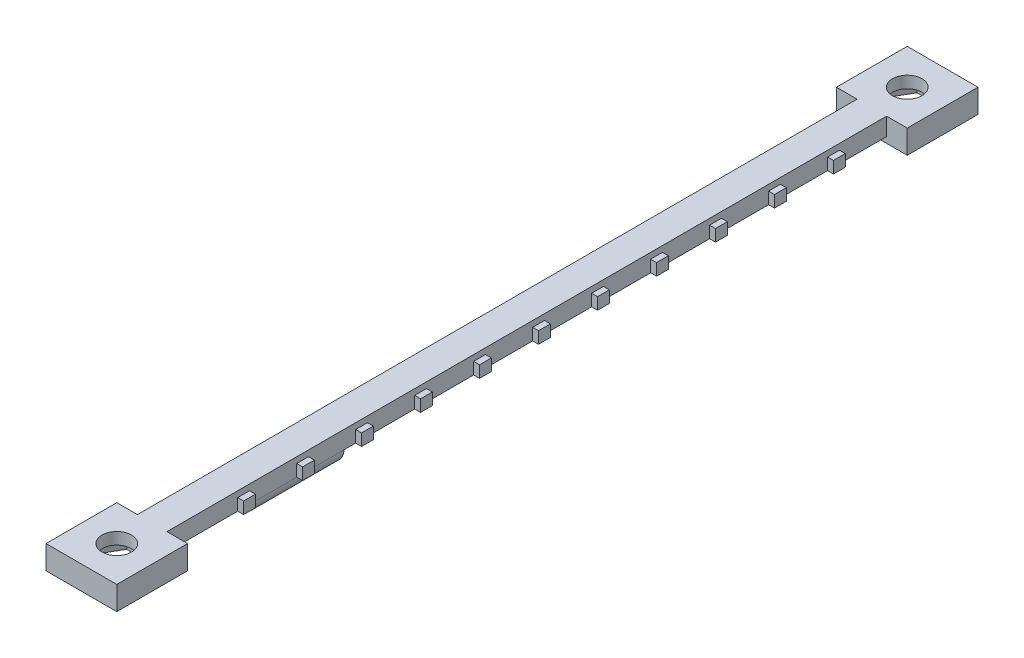
SolidWorks part; units mm, degrees
ref_plane "Front Plane" through (0, 0, 0) normal (0, 0, 1) x (1, 0, 0)
ref_plane "Top Plane" through (0, 0, 0) normal (0, 1, 0) x (1, 0, 0)
ref_plane "Right Plane" through (0, 0, 0) normal (1, 0, 0) x (0, 0, -1)
sketch "Sketch1" plane through (0, 0, 0) normal (0, 1, 0) x (1, 0, 0)
  line L0 (7.2267, 6.096) -> (7.2267, 18.096)
  line L1 (12.2267, 6.096) -> (12.2267, 18.096)
  line L2 (7.2267, 128.096) -> (3.7267, 128.096)
  line L3 (12.2267, 128.096) -> (15.7267, 128.096)
  line L4 (3.7267, 128.096) -> (3.7267, 140.096)
  line L5 (15.7267, 128.096) -> (15.7267, 140.096)
  line L6 (3.7267, 140.096) -> (15.7267, 140.096)
  line L7 (7.2267, 6.096) -> (3.7267, 6.096)
  line L8 (12.2267, 6.096) -> (15.7267, 6.096)
  line L9 (3.7267, 6.096) -> (3.7267, -5.904)
  line L10 (15.7267, 6.096) -> (15.7267, -5.904)
  line L11 (3.7267, -5.904) -> (15.7267, -5.904)
  line L12 (7.2267, 120.096) -> (7.2267, 128.096)
  line L13 (7.2267, 6.096) -> (7.2267, 128.096) construction
  line L14 (-994.5233, 128.096) -> (49005.4767, 128.096) construction
  line L15 (6.2267, 120.096) -> (7.2267, 120.096)
  line L18 (6.2267, 118.096) -> (7.2267, 118.096)
  line L19 (6.2267, 110.096) -> (7.2267, 110.096)
  line L20 (6.2267, 108.096) -> (7.2267, 108.096)
  line L21 (6.2267, 100.096) -> (7.2267, 100.096)
  line L22 (6.2267, 98.096) -> (7.2267, 98.096)
  line L23 (6.2267, 90.096) -> (7.2267, 90.096)
  line L24 (6.2267, 88.096) -> (7.2267, 88.096)
  line L25 (6.2267, 80.096) -> (7.2267, 80.096)
  line L26 (6.2267, 78.096) -> (7.2267, 78.096)
  line L27 (6.2267, 70.096) -> (7.2267, 70.096)
  line L28 (6.2267, 68.096) -> (7.2267, 68.096)
  line L29 (6.2267, 60.096) -> (7.2267, 60.096)
  line L30 (6.2267, 58.096) -> (7.2267, 58.096)
  line L31 (6.2267, 50.096) -> (7.2267, 50.096)
  line L32 (6.2267, 48.096) -> (7.2267, 48.096)
  line L33 (6.2267, 40.096) -> (7.2267, 40.096)
  line L34 (6.2267, 38.096) -> (7.2267, 38.096)
  line L35 (6.2267, 30.096) -> (7.2267, 30.096)
  line L36 (6.2267, 28.096) -> (7.2267, 28.096)
  line L37 (6.2267, 20.096) -> (7.2267, 20.096)
  line L38 (6.2267, 18.096) -> (7.2267, 18.096)
  line L39 (-994.5233, 118.096) -> (49005.4767, 118.096) construction
  line L40 (-994.5233, 120.096) -> (49005.4767, 120.096) construction
  line L41 (12.2267, 120.096) -> (12.2267, 128.096)
  line L42 (12.2267, 6.096) -> (12.2267, 128.096) construction
  line L43 (6.2267, 118.096) -> (6.2267, 120.096)
  line L44 (12.2267, 118.096) -> (13.2267, 118.096)
  line L45 (12.2267, 120.096) -> (13.2267, 120.096)
  line L46 (7.2267, 110.096) -> (7.2267, 118.096)
  line L47 (12.2267, 110.096) -> (12.2267, 118.096)
  line L48 (13.2267, 118.096) -> (13.2267, 120.096)
  line L49 (-994.5233, 110.096) -> (49005.4767, 110.096) construction
  line L50 (-994.5233, 108.096) -> (49005.4767, 108.096) construction
  line L51 (13.2267, 108.096) -> (13.2267, 110.096)
  line L52 (-994.5233, 100.096) -> (49005.4767, 100.096) construction
  line L53 (12.2267, 110.096) -> (13.2267, 110.096)
  line L54 (12.2267, 108.096) -> (13.2267, 108.096)
  line L55 (12.2267, 100.096) -> (13.2267, 100.096)
  line L56 (12.2267, 98.096) -> (13.2267, 98.096)
  line L57 (-994.5233, 98.096) -> (49005.4767, 98.096) construction
  line L58 (12.2267, 90.096) -> (13.2267, 90.096)
  line L59 (-994.5233, 90.096) -> (49005.4767, 90.096) construction
  line L60 (12.2267, 88.096) -> (13.2267, 88.096)
  line L61 (-994.5233, 88.096) -> (49005.4767, 88.096) construction
  line L62 (12.2267, 80.096) -> (13.2267, 80.096)
  line L63 (-994.5233, 80.096) -> (49005.4767, 80.096) construction
  line L64 (12.2267, 78.096) -> (13.2267, 78.096)
  line L65 (-994.5233, 78.096) -> (49005.4767, 78.096) construction
  line L66 (12.2267, 70.096) -> (13.2267, 70.096)
  line L67 (-994.5233, 70.096) -> (49005.4767, 70.096) construction
  line L68 (12.2267, 68.096) -> (13.2267, 68.096)
  line L69 (-994.5233, 68.096) -> (49005.4767, 68.096) construction
  line L70 (12.2267, 60.096) -> (13.2267, 60.096)
  line L71 (-994.5233, 60.096) -> (49005.4767, 60.096) construction
  line L72 (12.2267, 58.096) -> (13.2267, 58.096)
  line L73 (-994.5233, 58.096) -> (49005.4767, 58.096) construction
  line L74 (12.2267, 50.096) -> (13.2267, 50.096)
  line L75 (-994.5233, 50.096) -> (49005.4767, 50.096) construction
  line L76 (12.2267, 48.096) -> (13.2267, 48.096)
  line L77 (-994.5233, 48.096) -> (49005.4767, 48.096) construction
  line L78 (12.2267, 40.096) -> (13.2267, 40.096)
  line L79 (-994.5233, 40.096) -> (49005.4767, 40.096) construction
  line L80 (12.2267, 38.096) -> (13.2267, 38.096)
  line L81 (-994.5233, 38.096) -> (49005.4767, 38.096) construction
  line L82 (12.2267, 30.096) -> (13.2267, 30.096)
  line L83 (-994.5233, 30.096) -> (49005.4767, 30.096) construction
  line L84 (12.2267, 28.096) -> (13.2267, 28.096)
  line L85 (-994.5233, 28.096) -> (49005.4767, 28.096) construction
  line L86 (12.2267, 20.096) -> (13.2267, 20.096)
  line L87 (-994.5233, 20.096) -> (49005.4767, 20.096) construction
  line L88 (12.2267, 18.096) -> (13.2267, 18.096)
  line L89 (-994.5233, 18.096) -> (49005.4767, 18.096) construction
  line L90 (13.2267, 18.096) -> (13.2267, 20.096)
  line L91 (6.2267, 108.096) -> (6.2267, 110.096)
  line L92 (12.2267, 100.096) -> (12.2267, 108.096)
  line L93 (7.2267, 100.096) -> (7.2267, 108.096)
  line L94 (7.2267, 90.096) -> (7.2267, 98.096)
  line L95 (12.2267, 90.096) -> (12.2267, 98.096)
  line L96 (13.2267, 98.096) -> (13.2267, 100.096)
  line L97 (6.2267, 98.096) -> (6.2267, 100.096)
  line L98 (12.2267, 80.096) -> (12.2267, 88.096)
  line L99 (7.2267, 80.096) -> (7.2267, 88.096)
  line L100 (7.2267, 70.096) -> (7.2267, 78.096)
  line L101 (12.2267, 70.096) -> (12.2267, 78.096)
  line L102 (12.2267, 60.096) -> (12.2267, 68.096)
  line L103 (7.2267, 60.096) -> (7.2267, 68.096)
  line L104 (13.2267, 88.096) -> (13.2267, 90.096)
  line L105 (13.2267, 78.096) -> (13.2267, 80.096)
  line L106 (13.2267, 68.096) -> (13.2267, 70.096)
  line L107 (13.2267, 58.096) -> (13.2267, 60.096)
  line L108 (6.2267, 58.096) -> (6.2267, 60.096)
  line L109 (6.2267, 68.096) -> (6.2267, 70.096)
  line L110 (6.2267, 78.096) -> (6.2267, 80.096)
  line L111 (6.2267, 88.096) -> (6.2267, 90.096)
  line L112 (12.2267, 50.096) -> (12.2267, 58.096)
  line L113 (7.2267, 50.096) -> (7.2267, 58.096)
  line L114 (7.2267, 40.096) -> (7.2267, 48.096)
  line L115 (12.2267, 40.096) -> (12.2267, 48.096)
  line L116 (7.2267, 30.096) -> (7.2267, 38.096)
  line L117 (12.2267, 30.096) -> (12.2267, 38.096)
  line L118 (7.2267, 20.096) -> (7.2267, 28.096)
  line L119 (12.2267, 20.096) -> (12.2267, 28.096)
  line L120 (6.2267, 18.096) -> (6.2267, 20.096)
  line L121 (6.2267, 28.096) -> (6.2267, 30.096)
  line L122 (6.2267, 38.096) -> (6.2267, 40.096)
  line L123 (6.2267, 48.096) -> (6.2267, 50.096)
  line L124 (13.2267, 48.096) -> (13.2267, 50.096)
  line L125 (13.2267, 28.096) -> (13.2267, 30.096)
  line L126 (13.2267, 38.096) -> (13.2267, 40.096)
  point P20 (5.4767, 128.096)
  dimension "D1" = 5
  dimension "D4" = 8
  dimension "D5" = 2
  dimension "D6" = 10
  dimension "D7" = 20
  dimension "D8" = 40
  dimension "D9" = 40
extrude "Boss-Extrude1" add sketch "Sketch1" along normal blind 2
sketch "Sketch2" plane through (0, 2, 0) normal (0, 1, 0) x (1, 0, 0)
  line L0 (3.7267, 140.096) -> (15.7267, 140.096)
  line L1 (15.7267, 140.096) -> (15.7267, 128.096)
  line L2 (15.7267, 128.096) -> (12.2267, 128.096)
  line L3 (12.2267, 128.096) -> (15.7267, 128.096) construction
  line L4 (12.2267, 128.096) -> (12.2267, 6.096)
  line L5 (12.2267, 6.096) -> (15.7267, 6.096)
  line L6 (15.7267, 6.096) -> (15.7267, -5.904)
  line L7 (3.7267, -5.904) -> (15.7267, -5.904) construction
  line L8 (15.7267, -5.904) -> (15.7267, 6.096) construction
  line L9 (15.7267, -5.904) -> (3.7267, -5.904)
  line L10 (3.7267, 6.096) -> (3.7267, -5.904) construction
  line L11 (3.7267, -5.904) -> (3.7267, 6.096)
  line L12 (3.7267, 6.096) -> (7.2267, 6.096)
  line L13 (7.2267, 6.096) -> (7.2267, 128.096)
  line L14 (7.2267, 128.096) -> (3.7267, 128.096)
  line L15 (3.7267, 128.096) -> (7.2267, 128.096) construction
  line L16 (3.7267, 140.096) -> (3.7267, 128.096) construction
  line L17 (3.7267, 128.096) -> (3.7267, 140.096)
extrude "Boss-Extrude2" add sketch "Sketch2" along normal blind 1
sketch "Sketch3" plane through (0, 0, 0) normal (0, -1, 0) x (-1, 0, 0)
  line L0 (-15.7267, 128.096) -> (-3.7267, 128.096)
  line L1 (-12.2267, 128.096) -> (-15.7267, 128.096) construction
  line L2 (-15.7267, 128.096) -> (-15.7267, 140.096) construction
  line L3 (-3.7267, 128.096) -> (-3.7267, 140.096)
  line L4 (-3.7267, 140.096) -> (-3.7267, 128.096) construction
  line L5 (-15.7267, 140.096) -> (-3.7267, 140.096) construction
  line L6 (-3.7267, 140.096) -> (-15.7267, 140.096)
  line L7 (-15.7267, 140.096) -> (-15.7267, 128.096)
  line L8 (-3.7267, -5.904) -> (-3.7267, 6.096)
  line L9 (-3.7267, 6.096) -> (-15.7267, 6.096)
  line L10 (-15.7267, 6.096) -> (-15.7267, -5.904)
  line L11 (-15.7267, -5.904) -> (-3.7267, -5.904)
extrude "Boss-Extrude3" add sketch "Sketch3" along normal blind 1 contours L11 L8 L9 L10 | L7 L0 L3 L6
sketch "Sketch4" plane through (0, -1, 0) normal (0, -1, 0) x (-1, 0, 0)
  line L0 (-1015.7267, 134.096) -> (48984.2733, 134.096) construction
  line L1 (-15.7267, 140.096) -> (-15.7267, 128.096) construction
  line L2 (-9.7267, -859.904) -> (-9.7267, 49140.096) construction
  line L3 (-3.7267, 140.096) -> (-15.7267, 140.096) construction
  line L4 (-1015.7267, 0.096) -> (48984.2733, 0.096) construction
  line L11 (-7.3651, 138.096) -> (-11.9839, 138.096)
  line L12 (-11.9839, 138.096) -> (-14.2933, 134.096)
  line L13 (-14.2933, 134.096) -> (-11.9839, 130.096)
  line L14 (-11.9839, 130.096) -> (-7.3651, 130.096)
  line L15 (-7.3651, 130.096) -> (-5.0557, 134.096)
  line L16 (-5.0557, 134.096) -> (-7.3651, 138.096)
  line L17 (-15.7267, 6.096) -> (-15.7267, -5.904) construction
  line L19 (-7.4173, 4.096) -> (-12.0361, 4.096)
  line L20 (-12.0361, 4.096) -> (-14.3455, 0.096)
  line L21 (-14.3455, 0.096) -> (-12.0361, -3.904)
  line L22 (-12.0361, -3.904) -> (-7.4173, -3.904)
  line L23 (-7.4173, -3.904) -> (-5.1079, 0.096)
  line L24 (-5.1079, 0.096) -> (-7.4173, 4.096)
  circle A1 centre (-9.6745, 134.096) radius 4 construction
  circle A2 centre (-9.7267, 0.096) radius 4 construction
  point P5 (-15.7267, 134.096)
  point P10 (-9.7267, 140.096)
  point P31 (-15.7267, 0.096)
extrude "Cut-Extrude1" cut sketch "Sketch4" against normal blind 2 contours L11 L12 L13 L14 L15 L16 | L19 L20 L21 L22 L23 L24
sketch "Sketch5" plane through (0, 1, 0) normal (0, -1, 0) x (-1, 0, 0)
  line L0 (-1005.0557, 134.096) -> (48994.9443, 134.096) construction
  line L1 (-1005.1079, 0.096) -> (48994.8921, 0.096) construction
  line L2 (-9.7267, -995.904) -> (-9.7267, 49004.096) construction
  line L3 (-7.4173, 4.096) -> (-12.0361, 4.096) construction
  circle A0 centre (-9.7267, 0.096) radius 2.5
  circle A1 centre (-9.7267, 134.096) radius 2.5
  point P11 (-9.7267, 4.096)
extrude "Cut-Extrude2" cut sketch "Sketch5" against normal blind 5 contours A1 | A0
sketch "Sketch6" plane through (0, 0, 0) normal (0, -1, 0) x (-1, 0, 0)
  line L0 (-1006.1015, 6.096) -> (48993.8985, 6.096) construction
  line L2 (-1004.9212, 128.096) -> (48995.0788, 128.096) construction
  line L4 (-11.2267, 21.096) -> (-8.2267, 21.096)
  line L5 (-11.2267, 36.096) -> (-8.2267, 36.096)
  line L11 (-12.2267, 21.096) -> (-12.2267, 36.096) construction
  line L14 (-11.2267, 21.096) -> (-11.2267, 36.096)
  line L16 (-8.2267, 21.096) -> (-8.2267, 36.096)
  line L18 (-7.2267, 21.096) -> (-7.2267, 36.096) construction
  line L20 (-1006.1015, 21.096) -> (48993.8985, 21.096) construction
  line L21 (-1006.1015, 36.096) -> (48993.8985, 36.096) construction
  dimension "D1" = 15
  dimension "D2" = 15
extrude "Boss-Extrude4" add sketch "Sketch6" along normal blind 5 contours L4 L16 L5 L14
sketch "Sketch7" plane through (0, 0, -36.096) normal (0, 0, -1) x (-1, 0, 0)
  line L0 (-8.2267, -5) -> (-11.2267, -5)
  line L1 (-11.2267, -5) -> (-11.2267, -1)
  line L2 (-3.7267, -1) -> (-15.7267, -1) construction
  line L3 (-11.2267, -5) -> (-11.2267, 0) construction
  line L4 (-11.2267, -1) -> (-8.2267, -1)
  line L5 (-8.2267, -5) -> (-8.2267, 0) construction
  line L6 (-8.2267, -1) -> (-8.2267, -5)
  ellipse E0 centre (-9.7267, -1) end of major axis (-9.7267, -5) minor radius 1.5 (-11.2267, -1) -> (-8.2267, -1) ccw
  line M2 (-11.2267, 0) -> (-11.2267, -5)
  line M3 (-11.2267, -5) -> (-8.2267, -5)
  line M4 (-8.2267, -5) -> (-8.2267, 0)
extrude "Cut-Extrude3" cut sketch "Sketch7" against normal blind 30 contours E0 L0 M4 | E0 M2 M3
sketch "Sketch8" plane through (0, 0, -36.096) normal (0, 0, -1) x (-1, 0, 0)
  line L0 (-11.2267, -1) -> (-8.2267, -1)
  line L2 (-11.2267, -7) -> (-8.2267, -7)
  line L3 (-11.2267, -1) -> (-11.2267, -7)
  line L4 (-8.2267, -1) -> (-8.2267, -7)
  line L5 (-1008.4727, -7) -> (48991.5273, -7) construction
  line L6 (-1008.4727, -1) -> (48991.5273, -1) construction
  dimension "D1" = 6
sketch "Sketch9" plane through (0, 0, -21.096) normal (0, 0, 1) x (1, 0, 0)
  line L0 (11.2267, 0) -> (11.2267, -7)
  line L1 (11.2267, 0) -> (8.2267, 0)
  line L2 (11.2267, -7) -> (8.2267, -7)
  line L3 (8.2267, -7) -> (8.2267, 0)
extrude "Cut-Extrude5" cut sketch "Sketch9" against normal blind 20 contours L3 L1 L0 L2
sketch "Sketch10" plane through (0, 0, 0) normal (0, -1, 0) x (-1, 0, 0)
  line L0 (-1005.9767, 36.096) -> (48994.0233, 36.096) construction
  line L1 (-3.7267, 6.096) -> (-8.2267, 6.096) construction
  line L2 (-7.2267, 21.096) -> (-7.2267, 36.096)
  line L3 (-7.2267, 28.096) -> (-7.2267, 20.096) construction
  line L4 (-12.2267, 21.096) -> (-12.2267, 36.096)
  line L5 (-12.2267, 20.096) -> (-12.2267, 28.096) construction
  line L6 (-12.2267, 21.096) -> (-7.2267, 21.096)
  line L7 (-12.2267, 36.096) -> (-7.2267, 36.096)
  line L8 (-1005.9767, 21.096) -> (48994.0233, 21.096) construction
  point P5 (-5.9767, 6.096)
  point P10 (-7.2267, 24.096)
  point P15 (-12.2267, 24.096)
  dimension "D2" = 15
extrude "Boss-Extrude5" add sketch "Sketch10" along normal blind 3
sketch "Sketch11" plane through (0, 0, -36.096) normal (0, 0, -1) x (-1, 0, 0)
  line L2 (-7.2267, 0) -> (-7.2267, -3)
  line L4 (-12.2267, 0) -> (-12.2267, -3)
  line L11 (-12.2267, 0) -> (-7.2267, 0) construction
  line L12 (-7.2267, -3) -> (-12.2267, -3)
  line L13 (-12.2267, 0) -> (-7.2267, 0)
  circle A0 centre (-9.7267, 0) radius 2.5
  point P11 (-9.7267, -3)
  line M5 (-12.2267, 0) -> (-12.2267, -3)
  line M6 (-12.2267, -3) -> (-7.2267, -3)
  line M7 (-7.2267, -3) -> (-7.2267, 0)
extrude "Cut-Extrude7" cut sketch "Sketch11" against normal blind 20 contours A0 M5 M6 M7
